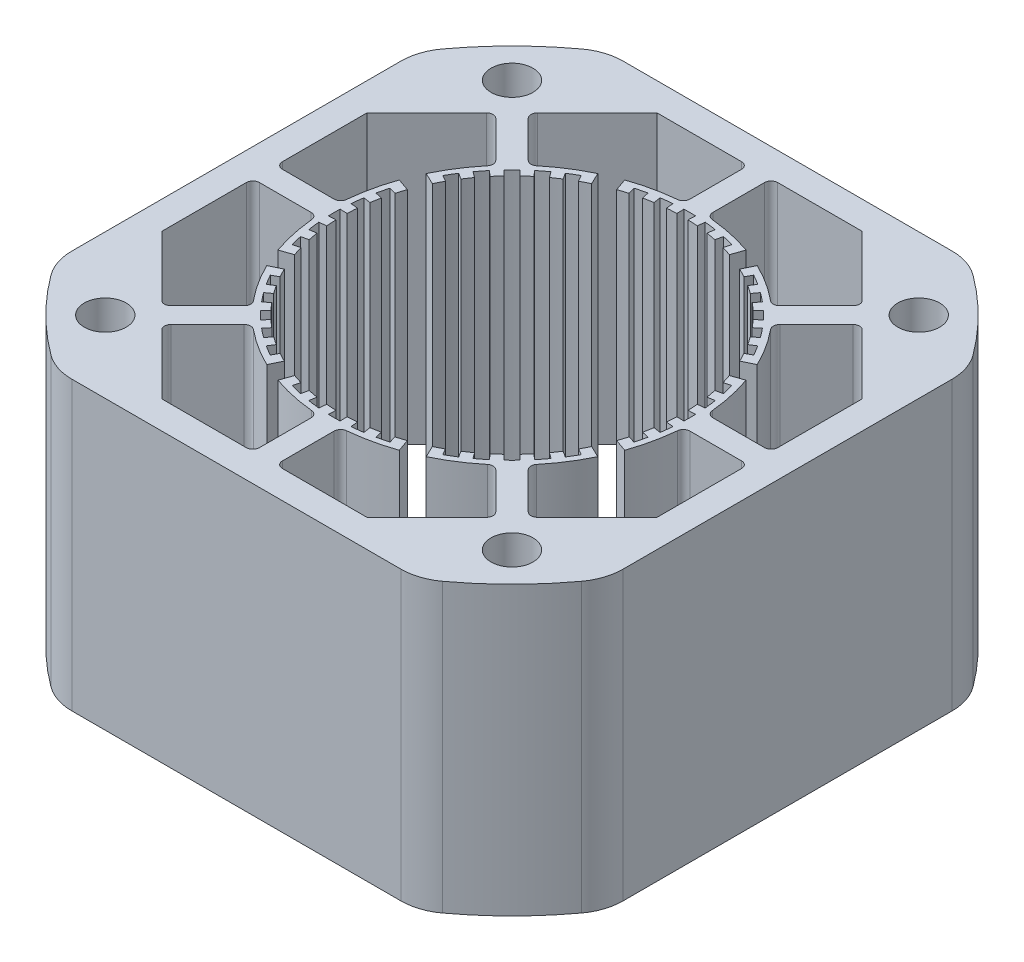
SolidWorks part; units mm, degrees
ref_plane "Front" through (0, 0, 0) normal (0, 0, 1) x (1, 0, 0)
ref_plane "Top" through (0, 0, 0) normal (0, 1, 0) x (1, 0, 0)
ref_plane "Right" through (0, 0, 0) normal (1, 0, 0) x (0, 0, -1)
ref_plane "Plane1" through (0, 10.95, 0) normal (0, 1, 0) x (1, 0, 0)
sketch "Sketch1" plane through (0, 10.95, 0) normal (0, 1, 0) x (1, 0, 0)
  line L0 (-0.875, -14.4347) -> (-0.875, -18.375)
  line L1 (-1.375, -18.875) -> (-7.8183, -18.875)
  line L2 (-7.8183, -18.875) -> (-12.3744, -14.3189)
  line L3 (-12.3744, -13.6118) -> (-9.5881, -10.8256)
  line L4 (-6.0745, -12.6135) -> (-5.6406, -11.7126)
  line L5 (-6.3066, -11.3678) -> (-6.5735, -11.8487)
  line L6 (-7.3337, -11.3938) -> (-7.036, -10.9313)
  line L7 (-7.6547, -10.5074) -> (-7.9786, -10.9519)
  line L8 (-8.6772, -10.4071) -> (-8.325, -9.9847)
  line L9 (-8.887, -9.488) -> (-9.2629, -9.8894)
  line L10 (-9.8894, -9.2629) -> (-9.488, -8.887)
  line L11 (-9.9847, -8.325) -> (-10.4071, -8.6772)
  line L12 (-10.9519, -7.9786) -> (-10.5074, -7.6547)
  line L13 (-10.9313, -7.036) -> (-11.3938, -7.3337)
  line L14 (-11.8487, -6.5735) -> (-11.3678, -6.3066)
  line L15 (-11.7126, -5.6406) -> (-12.6135, -6.0745)
  line L16 (-10.8256, -9.5881) -> (-13.6118, -12.3744)
  line L17 (-14.3189, -12.3744) -> (-18.875, -7.8183)
  line L18 (-18.875, -7.8183) -> (-18.875, -1.375)
  line L19 (-18.375, -0.875) -> (-14.4347, -0.875)
  line L20 (-13.2144, -4.6238) -> (-12.2705, -4.2935)
  line L21 (-12.4977, -3.5788) -> (-13.0264, -3.7302)
  line L22 (-13.2424, -2.8709) -> (-12.7049, -2.7544)
  line L23 (-12.8426, -2.0171) -> (-13.3859, -2.1025)
  line L24 (-13.4947, -1.2232) -> (-12.9469, -1.1736)
  line L25 (-12.9931, -0.425) -> (-13.5428, -0.443)
  line L26 (-13.5428, 0.443) -> (-12.9931, 0.425)
  line L27 (-12.9469, 1.1736) -> (-13.4947, 1.2232)
  line L28 (-13.3859, 2.1025) -> (-12.8426, 2.0171)
  line L29 (-12.7049, 2.7544) -> (-13.2424, 2.8709)
  line L30 (-13.0264, 3.7302) -> (-12.4977, 3.5788)
  line L31 (-12.2705, 4.2935) -> (-13.2144, 4.6238)
  line L32 (-14.4347, 0.875) -> (-18.375, 0.875)
  line L33 (-18.875, 1.375) -> (-18.875, 7.8183)
  line L34 (-18.875, 7.8183) -> (-14.3189, 12.3744)
  line L35 (-13.6118, 12.3744) -> (-10.8256, 9.5881)
  line L36 (-12.6135, 6.0745) -> (-11.7126, 5.6406)
  line L37 (-11.3678, 6.3066) -> (-11.8487, 6.5735)
  line L38 (-11.3938, 7.3337) -> (-10.9313, 7.036)
  line L39 (-10.5074, 7.6547) -> (-10.9519, 7.9786)
  line L40 (-10.4071, 8.6772) -> (-9.9847, 8.325)
  line L41 (-9.488, 8.887) -> (-9.8894, 9.2629)
  line L42 (-9.2629, 9.8894) -> (-8.887, 9.488)
  line L43 (-8.325, 9.9847) -> (-8.6772, 10.4071)
  line L44 (-7.9786, 10.9519) -> (-7.6547, 10.5074)
  line L45 (-7.036, 10.9313) -> (-7.3337, 11.3938)
  line L46 (-6.5735, 11.8487) -> (-6.3066, 11.3678)
  line L47 (-5.6406, 11.7126) -> (-6.0745, 12.6135)
  line L48 (-9.5881, 10.8256) -> (-12.3744, 13.6118)
  line L49 (-12.3744, 14.3189) -> (-7.8183, 18.875)
  line L50 (-7.8183, 18.875) -> (-1.375, 18.875)
  line L51 (-0.875, 18.375) -> (-0.875, 14.4347)
  line L52 (-4.6238, 13.2144) -> (-4.2935, 12.2705)
  line L53 (-3.5788, 12.4977) -> (-3.7302, 13.0264)
  line L54 (-2.8709, 13.2424) -> (-2.7544, 12.7049)
  line L55 (-2.0171, 12.8426) -> (-2.1025, 13.3859)
  line L56 (-1.2232, 13.4947) -> (-1.1736, 12.9469)
  line L57 (-0.425, 12.9931) -> (-0.443, 13.5428)
  line L58 (0.443, 13.5428) -> (0.425, 12.9931)
  line L59 (1.1736, 12.9469) -> (1.2232, 13.4947)
  line L60 (2.1025, 13.3859) -> (2.0171, 12.8426)
  line L61 (2.7544, 12.7049) -> (2.8709, 13.2424)
  line L62 (3.7302, 13.0264) -> (3.5788, 12.4977)
  line L63 (4.2935, 12.2705) -> (4.6238, 13.2144)
  line L64 (0.875, 14.4347) -> (0.875, 18.375)
  line L65 (1.375, 18.875) -> (7.8183, 18.875)
  line L66 (7.8183, 18.875) -> (12.3744, 14.3189)
  line L67 (12.3744, 13.6118) -> (9.5881, 10.8256)
  line L68 (6.0745, 12.6135) -> (5.6406, 11.7126)
  line L69 (6.3066, 11.3678) -> (6.5735, 11.8487)
  line L70 (7.3337, 11.3938) -> (7.036, 10.9313)
  line L71 (7.6547, 10.5074) -> (7.9786, 10.9519)
  line L72 (8.6772, 10.4071) -> (8.325, 9.9847)
  line L73 (8.887, 9.488) -> (9.2629, 9.8894)
  line L74 (9.8894, 9.2629) -> (9.488, 8.887)
  line L75 (9.9847, 8.325) -> (10.4071, 8.6772)
  line L76 (10.9519, 7.9786) -> (10.5074, 7.6547)
  line L77 (10.9313, 7.036) -> (11.3938, 7.3337)
  line L78 (11.8487, 6.5735) -> (11.3678, 6.3066)
  line L79 (11.7126, 5.6406) -> (12.6135, 6.0745)
  line L80 (10.8256, 9.5881) -> (13.6118, 12.3744)
  line L81 (14.3189, 12.3744) -> (18.875, 7.8183)
  line L82 (18.875, 7.8183) -> (18.875, 1.375)
  line L83 (18.375, 0.875) -> (14.4347, 0.875)
  line L84 (13.2144, 4.6238) -> (12.2705, 4.2935)
  line L85 (12.4977, 3.5788) -> (13.0264, 3.7302)
  line L86 (13.2424, 2.8709) -> (12.7049, 2.7544)
  line L87 (12.8426, 2.0171) -> (13.3859, 2.1025)
  line L88 (13.4947, 1.2232) -> (12.9469, 1.1736)
  line L89 (12.9931, 0.425) -> (13.5428, 0.443)
  line L90 (13.5428, -0.443) -> (12.9931, -0.425)
  line L91 (12.9469, -1.1736) -> (13.4947, -1.2232)
  line L92 (13.3859, -2.1025) -> (12.8426, -2.0171)
  line L93 (12.7049, -2.7544) -> (13.2424, -2.8709)
  line L94 (13.0264, -3.7302) -> (12.4977, -3.5788)
  line L95 (12.2705, -4.2935) -> (13.2144, -4.6238)
  line L96 (14.4347, -0.875) -> (18.375, -0.875)
  line L97 (18.875, -1.375) -> (18.875, -7.8183)
  line L98 (18.875, -7.8183) -> (14.3189, -12.3744)
  line L99 (13.6118, -12.3744) -> (10.8256, -9.5881)
  line L100 (12.6135, -6.0745) -> (11.7126, -5.6406)
  line L101 (11.3678, -6.3066) -> (11.8487, -6.5735)
  line L102 (11.3938, -7.3337) -> (10.9313, -7.036)
  line L103 (10.5074, -7.6547) -> (10.9519, -7.9786)
  line L104 (10.4071, -8.6772) -> (9.9847, -8.325)
  line L105 (9.488, -8.887) -> (9.8894, -9.2629)
  line L106 (9.2629, -9.8894) -> (8.887, -9.488)
  line L107 (8.325, -9.9847) -> (8.6772, -10.4071)
  line L108 (7.9786, -10.9519) -> (7.6547, -10.5074)
  line L109 (7.036, -10.9313) -> (7.3337, -11.3938)
  line L110 (6.5735, -11.8487) -> (6.3066, -11.3678)
  line L111 (5.6406, -11.7126) -> (6.0745, -12.6135)
  line L112 (9.5881, -10.8256) -> (12.3744, -13.6118)
  line L113 (12.3744, -14.3189) -> (7.8183, -18.875)
  line L114 (7.8183, -18.875) -> (1.375, -18.875)
  line L115 (0.875, -18.375) -> (0.875, -14.4347)
  line L116 (4.6238, -13.2144) -> (4.2935, -12.2705)
  line L117 (3.5788, -12.4977) -> (3.7302, -13.0264)
  line L118 (2.8709, -13.2424) -> (2.7544, -12.7049)
  line L119 (2.0171, -12.8426) -> (2.1025, -13.3859)
  line L120 (1.2232, -13.4947) -> (1.1736, -12.9469)
  line L121 (0.425, -12.9931) -> (0.443, -13.5428)
  line L122 (-0.443, -13.5428) -> (-0.425, -12.9931)
  line L123 (-1.1736, -12.9469) -> (-1.2232, -13.4947)
  line L124 (-2.1025, -13.3859) -> (-2.0171, -12.8426)
  line L125 (-2.7544, -12.7049) -> (-2.8709, -13.2424)
  line L126 (-3.7302, -13.0264) -> (-3.5788, -12.4977)
  line L127 (-4.2935, -12.2705) -> (-4.6238, -13.2144)
  line L128 (21, -12.5406) -> (21, 12.5406)
  line L129 (12.5406, 21) -> (-12.5406, 21)
  line L130 (-21, 12.5406) -> (-21, -12.5406)
  line L131 (-12.5406, -21) -> (12.5406, -21)
  arc A0 (-0.875, -18.375) -> (-1.375, -18.875) centre (-1.375, -18.375) cw
  arc A1 (-12.3744, -14.3189) -> (-12.3744, -13.6118) centre (-12.0208, -13.9654) cw
  arc A2 (-9.5881, -10.8256) -> (-8.9161, -10.7936) centre (-9.2346, -11.1791) cw
  arc A3 (-8.9161, -10.7936) -> (-6.0745, -12.6135) centre (0, 0) ccw
  arc A4 (-5.6406, -11.7126) -> (-6.3066, -11.3678) centre (0, 0) cw
  arc A5 (-6.5735, -11.8487) -> (-7.3337, -11.3938) centre (0, 0) cw
  arc A6 (-7.036, -10.9313) -> (-7.6547, -10.5074) centre (0, 0) cw
  arc A7 (-7.9786, -10.9519) -> (-8.6772, -10.4071) centre (0, 0) cw
  arc A8 (-8.325, -9.9847) -> (-8.887, -9.488) centre (0, 0) cw
  arc A9 (-9.2629, -9.8894) -> (-9.8894, -9.2629) centre (0, 0) cw
  arc A10 (-9.488, -8.887) -> (-9.9847, -8.325) centre (0, 0) cw
  arc A11 (-10.4071, -8.6772) -> (-10.9519, -7.9786) centre (0, 0) cw
  arc A12 (-10.5074, -7.6547) -> (-10.9313, -7.036) centre (0, 0) cw
  arc A13 (-11.3938, -7.3337) -> (-11.8487, -6.5735) centre (0, 0) cw
  arc A14 (-11.3678, -6.3066) -> (-11.7126, -5.6406) centre (0, 0) cw
  arc A15 (-12.6135, -6.0745) -> (-10.7936, -8.9161) centre (0, 0) ccw
  arc A16 (-10.7936, -8.9161) -> (-10.8256, -9.5881) centre (-11.1791, -9.2346) cw
  arc A17 (-13.6118, -12.3744) -> (-14.3189, -12.3744) centre (-13.9654, -12.0208) cw
  arc A18 (-18.875, -1.375) -> (-18.375, -0.875) centre (-18.375, -1.375) cw
  arc A19 (-14.4347, -0.875) -> (-13.9369, -1.3276) centre (-14.4347, -1.375) cw
  arc A20 (-13.9369, -1.3276) -> (-13.2144, -4.6238) centre (0, 0) ccw
  arc A21 (-12.2705, -4.2935) -> (-12.4977, -3.5788) centre (0, 0) cw
  arc A22 (-13.0264, -3.7302) -> (-13.2424, -2.8709) centre (0, 0) cw
  arc A23 (-12.7049, -2.7544) -> (-12.8426, -2.0171) centre (0, 0) cw
  arc A24 (-13.3859, -2.1025) -> (-13.4947, -1.2232) centre (0, 0) cw
  arc A25 (-12.9469, -1.1736) -> (-12.9931, -0.425) centre (0, 0) cw
  arc A26 (-13.5428, -0.443) -> (-13.5428, 0.443) centre (0, 0) cw
  arc A27 (-12.9931, 0.425) -> (-12.9469, 1.1736) centre (0, 0) cw
  arc A28 (-13.4947, 1.2232) -> (-13.3859, 2.1025) centre (0, 0) cw
  arc A29 (-12.8426, 2.0171) -> (-12.7049, 2.7544) centre (0, 0) cw
  arc A30 (-13.2424, 2.8709) -> (-13.0264, 3.7302) centre (0, 0) cw
  arc A31 (-12.4977, 3.5788) -> (-12.2705, 4.2935) centre (0, 0) cw
  arc A32 (-13.2144, 4.6238) -> (-13.9369, 1.3276) centre (0, 0) ccw
  arc A33 (-13.9369, 1.3276) -> (-14.4347, 0.875) centre (-14.4347, 1.375) cw
  arc A34 (-18.375, 0.875) -> (-18.875, 1.375) centre (-18.375, 1.375) cw
  arc A35 (-14.3189, 12.3744) -> (-13.6118, 12.3744) centre (-13.9654, 12.0208) cw
  arc A36 (-10.8256, 9.5881) -> (-10.7936, 8.9161) centre (-11.1791, 9.2346) cw
  arc A37 (-10.7936, 8.9161) -> (-12.6135, 6.0745) centre (0, 0) ccw
  arc A38 (-11.7126, 5.6406) -> (-11.3678, 6.3066) centre (0, 0) cw
  arc A39 (-11.8487, 6.5735) -> (-11.3938, 7.3337) centre (0, 0) cw
  arc A40 (-10.9313, 7.036) -> (-10.5074, 7.6547) centre (0, 0) cw
  arc A41 (-10.9519, 7.9786) -> (-10.4071, 8.6772) centre (0, 0) cw
  arc A42 (-9.9847, 8.325) -> (-9.488, 8.887) centre (0, 0) cw
  arc A43 (-9.8894, 9.2629) -> (-9.2629, 9.8894) centre (0, 0) cw
  arc A44 (-8.887, 9.488) -> (-8.325, 9.9847) centre (0, 0) cw
  arc A45 (-8.6772, 10.4071) -> (-7.9786, 10.9519) centre (0, 0) cw
  arc A46 (-7.6547, 10.5074) -> (-7.036, 10.9313) centre (0, 0) cw
  arc A47 (-7.3337, 11.3938) -> (-6.5735, 11.8487) centre (0, 0) cw
  arc A48 (-6.3066, 11.3678) -> (-5.6406, 11.7126) centre (0, 0) cw
  arc A49 (-6.0745, 12.6135) -> (-8.9161, 10.7936) centre (0, 0) ccw
  arc A50 (-8.9161, 10.7936) -> (-9.5881, 10.8256) centre (-9.2346, 11.1791) cw
  arc A51 (-12.3744, 13.6118) -> (-12.3744, 14.3189) centre (-12.0208, 13.9654) cw
  arc A52 (-1.375, 18.875) -> (-0.875, 18.375) centre (-1.375, 18.375) cw
  arc A53 (-0.875, 14.4347) -> (-1.3276, 13.9369) centre (-1.375, 14.4347) cw
  arc A54 (-1.3276, 13.9369) -> (-4.6238, 13.2144) centre (0, 0) ccw
  arc A55 (-4.2935, 12.2705) -> (-3.5788, 12.4977) centre (0, 0) cw
  arc A56 (-3.7302, 13.0264) -> (-2.8709, 13.2424) centre (0, 0) cw
  arc A57 (-2.7544, 12.7049) -> (-2.0171, 12.8426) centre (0, 0) cw
  arc A58 (-2.1025, 13.3859) -> (-1.2232, 13.4947) centre (0, 0) cw
  arc A59 (-1.1736, 12.9469) -> (-0.425, 12.9931) centre (0, 0) cw
  arc A60 (-0.443, 13.5428) -> (0.443, 13.5428) centre (0, 0) cw
  arc A61 (0.425, 12.9931) -> (1.1736, 12.9469) centre (0, 0) cw
  arc A62 (1.2232, 13.4947) -> (2.1025, 13.3859) centre (0, 0) cw
  arc A63 (2.0171, 12.8426) -> (2.7544, 12.7049) centre (0, 0) cw
  arc A64 (2.8709, 13.2424) -> (3.7302, 13.0264) centre (0, 0) cw
  arc A65 (3.5788, 12.4977) -> (4.2935, 12.2705) centre (0, 0) cw
  arc A66 (4.6238, 13.2144) -> (1.3276, 13.9369) centre (0, 0) ccw
  arc A67 (1.3276, 13.9369) -> (0.875, 14.4347) centre (1.375, 14.4347) cw
  arc A68 (0.875, 18.375) -> (1.375, 18.875) centre (1.375, 18.375) cw
  arc A69 (12.3744, 14.3189) -> (12.3744, 13.6118) centre (12.0208, 13.9654) cw
  arc A70 (9.5881, 10.8256) -> (8.9161, 10.7936) centre (9.2346, 11.1791) cw
  arc A71 (8.9161, 10.7936) -> (6.0745, 12.6135) centre (0, 0) ccw
  arc A72 (5.6406, 11.7126) -> (6.3066, 11.3678) centre (0, 0) cw
  arc A73 (6.5735, 11.8487) -> (7.3337, 11.3938) centre (0, 0) cw
  arc A74 (7.036, 10.9313) -> (7.6547, 10.5074) centre (0, 0) cw
  arc A75 (7.9786, 10.9519) -> (8.6772, 10.4071) centre (0, 0) cw
  arc A76 (8.325, 9.9847) -> (8.887, 9.488) centre (0, 0) cw
  arc A77 (9.2629, 9.8894) -> (9.8894, 9.2629) centre (0, 0) cw
  arc A78 (9.488, 8.887) -> (9.9847, 8.325) centre (0, 0) cw
  arc A79 (10.4071, 8.6772) -> (10.9519, 7.9786) centre (0, 0) cw
  arc A80 (10.5074, 7.6547) -> (10.9313, 7.036) centre (0, 0) cw
  arc A81 (11.3938, 7.3337) -> (11.8487, 6.5735) centre (0, 0) cw
  arc A82 (11.3678, 6.3066) -> (11.7126, 5.6406) centre (0, 0) cw
  arc A83 (12.6135, 6.0745) -> (10.7936, 8.9161) centre (0, 0) ccw
  arc A84 (10.7936, 8.9161) -> (10.8256, 9.5881) centre (11.1791, 9.2346) cw
  arc A85 (13.6118, 12.3744) -> (14.3189, 12.3744) centre (13.9654, 12.0208) cw
  arc A86 (18.875, 1.375) -> (18.375, 0.875) centre (18.375, 1.375) cw
  arc A87 (14.4347, 0.875) -> (13.9369, 1.3276) centre (14.4347, 1.375) cw
  arc A88 (13.9369, 1.3276) -> (13.2144, 4.6238) centre (0, 0) ccw
  arc A89 (12.2705, 4.2935) -> (12.4977, 3.5788) centre (0, 0) cw
  arc A90 (13.0264, 3.7302) -> (13.2424, 2.8709) centre (0, 0) cw
  arc A91 (12.7049, 2.7544) -> (12.8426, 2.0171) centre (0, 0) cw
  arc A92 (13.3859, 2.1025) -> (13.4947, 1.2232) centre (0, 0) cw
  arc A93 (12.9469, 1.1736) -> (12.9931, 0.425) centre (0, 0) cw
  arc A94 (13.5428, 0.443) -> (13.5428, -0.443) centre (0, 0) cw
  arc A95 (12.9931, -0.425) -> (12.9469, -1.1736) centre (0, 0) cw
  arc A96 (13.4947, -1.2232) -> (13.3859, -2.1025) centre (0, 0) cw
  arc A97 (12.8426, -2.0171) -> (12.7049, -2.7544) centre (0, 0) cw
  arc A98 (13.2424, -2.8709) -> (13.0264, -3.7302) centre (0, 0) cw
  arc A99 (12.4977, -3.5788) -> (12.2705, -4.2935) centre (0, 0) cw
  arc A100 (13.2144, -4.6238) -> (13.9369, -1.3276) centre (0, 0) ccw
  arc A101 (13.9369, -1.3276) -> (14.4347, -0.875) centre (14.4347, -1.375) cw
  arc A102 (18.375, -0.875) -> (18.875, -1.375) centre (18.375, -1.375) cw
  arc A103 (14.3189, -12.3744) -> (13.6118, -12.3744) centre (13.9654, -12.0208) cw
  arc A104 (10.8256, -9.5881) -> (10.7936, -8.9161) centre (11.1791, -9.2346) cw
  arc A105 (10.7936, -8.9161) -> (12.6135, -6.0745) centre (0, 0) ccw
  arc A106 (11.7126, -5.6406) -> (11.3678, -6.3066) centre (0, 0) cw
  arc A107 (11.8487, -6.5735) -> (11.3938, -7.3337) centre (0, 0) cw
  arc A108 (10.9313, -7.036) -> (10.5074, -7.6547) centre (0, 0) cw
  arc A109 (10.9519, -7.9786) -> (10.4071, -8.6772) centre (0, 0) cw
  arc A110 (9.9847, -8.325) -> (9.488, -8.887) centre (0, 0) cw
  arc A111 (9.8894, -9.2629) -> (9.2629, -9.8894) centre (0, 0) cw
  arc A112 (8.887, -9.488) -> (8.325, -9.9847) centre (0, 0) cw
  arc A113 (8.6772, -10.4071) -> (7.9786, -10.9519) centre (0, 0) cw
  arc A114 (7.6547, -10.5074) -> (7.036, -10.9313) centre (0, 0) cw
  arc A115 (7.3337, -11.3938) -> (6.5735, -11.8487) centre (0, 0) cw
  arc A116 (6.3066, -11.3678) -> (5.6406, -11.7126) centre (0, 0) cw
  arc A117 (6.0745, -12.6135) -> (8.9161, -10.7936) centre (0, 0) ccw
  arc A118 (8.9161, -10.7936) -> (9.5881, -10.8256) centre (9.2346, -11.1791) cw
  arc A119 (12.3744, -13.6118) -> (12.3744, -14.3189) centre (12.0208, -13.9654) cw
  arc A120 (1.375, -18.875) -> (0.875, -18.375) centre (1.375, -18.375) cw
  arc A121 (0.875, -14.4347) -> (1.3276, -13.9369) centre (1.375, -14.4347) cw
  arc A122 (1.3276, -13.9369) -> (4.6238, -13.2144) centre (0, 0) ccw
  arc A123 (4.2935, -12.2705) -> (3.5788, -12.4977) centre (0, 0) cw
  arc A124 (3.7302, -13.0264) -> (2.8709, -13.2424) centre (0, 0) cw
  arc A125 (2.7544, -12.7049) -> (2.0171, -12.8426) centre (0, 0) cw
  arc A126 (2.1025, -13.3859) -> (1.2232, -13.4947) centre (0, 0) cw
  arc A127 (1.1736, -12.9469) -> (0.425, -12.9931) centre (0, 0) cw
  arc A128 (0.443, -13.5428) -> (-0.443, -13.5428) centre (0, 0) cw
  arc A129 (-0.425, -12.9931) -> (-1.1736, -12.9469) centre (0, 0) cw
  arc A130 (-1.2232, -13.4947) -> (-2.1025, -13.3859) centre (0, 0) cw
  arc A131 (-2.0171, -12.8426) -> (-2.7544, -12.7049) centre (0, 0) cw
  arc A132 (-2.8709, -13.2424) -> (-3.7302, -13.0264) centre (0, 0) cw
  arc A133 (-3.5788, -12.4977) -> (-4.2935, -12.2705) centre (0, 0) cw
  arc A134 (-4.6238, -13.2144) -> (-1.3276, -13.9369) centre (0, 0) ccw
  arc A135 (-1.3276, -13.9369) -> (-0.875, -14.4347) centre (-1.375, -14.4347) cw
  arc A136 (14.9151, -20.2189) -> (20.2189, -14.9151) centre (0, 0) ccw
  arc A137 (20.2189, -14.9151) -> (21, -12.5406) centre (17, -12.5406) ccw
  arc A138 (21, 12.5406) -> (20.2189, 14.9151) centre (17, 12.5406) ccw
  arc A139 (20.2189, 14.9151) -> (14.9151, 20.2189) centre (0, 0) ccw
  arc A140 (14.9151, 20.2189) -> (12.5406, 21) centre (12.5406, 17) ccw
  arc A141 (-12.5406, 21) -> (-14.9151, 20.2189) centre (-12.5406, 17) ccw
  arc A142 (-14.9151, 20.2189) -> (-20.2189, 14.9151) centre (0, 0) ccw
  arc A143 (-20.2189, 14.9151) -> (-21, 12.5406) centre (-17, 12.5406) ccw
  arc A144 (-21, -12.5406) -> (-20.2189, -14.9151) centre (-17, -12.5406) ccw
  arc A145 (-20.2189, -14.9151) -> (-14.9151, -20.2189) centre (0, 0) ccw
  arc A146 (-14.9151, -20.2189) -> (-12.5406, -21) centre (-12.5406, -17) ccw
  arc A147 (12.5406, -21) -> (14.9151, -20.2189) centre (12.5406, -17) ccw
sketch "Sketch10" plane through (0, 0, 0) normal (0, 1, 0) x (1, 0, 0)
  line L4 (12.5406, 21) -> (-12.5406, 21)
  line L5 (-21, 12.5406) -> (-21, -12.5406)
  line L6 (-12.5406, -21) -> (12.5406, -21)
  line L7 (21, -12.5406) -> (21, 12.5406)
  line L10 (7.8183, -18.875) -> (18.875, -7.8183)
  line L11 (18.875, -7.8183) -> (18.875, 7.8183)
  line L12 (18.875, 7.8183) -> (7.8183, 18.875)
  line L13 (7.8183, 18.875) -> (-7.8183, 18.875)
  line L14 (-7.8183, 18.875) -> (-18.875, 7.8183)
  line L15 (-18.875, 7.8183) -> (-18.875, -7.8183)
  line L16 (-18.875, -7.8183) -> (-7.8183, -18.875)
  line L17 (0, 21) -> (0, 0) construction
  line L18 (0, 0) -> (21, 0) construction
  line L19 (-7.8183, -18.875) -> (7.8183, -18.875)
  arc A12 (-12.5406, 21) -> (-14.9151, 20.2189) centre (-12.5406, 17) ccw
  arc A13 (-14.9151, 20.2189) -> (-20.2189, 14.9151) centre (0, 0) ccw
  arc A14 (-20.2189, 14.9151) -> (-21, 12.5406) centre (-17, 12.5406) ccw
  arc A15 (-21, -12.5406) -> (-20.2189, -14.9151) centre (-17, -12.5406) ccw
  arc A16 (-20.2189, -14.9151) -> (-14.9151, -20.2189) centre (0, 0) ccw
  arc A17 (-14.9151, -20.2189) -> (-12.5406, -21) centre (-12.5406, -17) ccw
  arc A18 (12.5406, -21) -> (14.9151, -20.2189) centre (12.5406, -17) ccw
  arc A19 (14.9151, -20.2189) -> (20.2189, -14.9151) centre (0, 0) ccw
  arc A20 (20.2189, -14.9151) -> (21, -12.5406) centre (17, -12.5406) ccw
  arc A21 (21, 12.5406) -> (20.2189, 14.9151) centre (17, 12.5406) ccw
  arc A22 (20.2189, 14.9151) -> (14.9151, 20.2189) centre (0, 0) ccw
  arc A23 (14.9151, 20.2189) -> (12.5406, 21) centre (12.5406, 17) ccw
  circle A24 centre (0, 0) radius 18.875 construction
  point P26 (-15.5, 15.5)
  point P39 (15.5, 15.5)
  point P40 (15.5, -15.5)
  point P41 (-15.5, -15.5)
  dimension "D3" = 25.125
  dimension "D4" = 4
  dimension "D1" = 42
  dimension "D2" = 42
  dimension "D5" = 37.75
  dimension "D6" = 31
  dimension "D7" = 31
extrude "Boss-Extrude2" add sketch "Sketch10" along normal blind 21.9
sketch "Sketch11" plane through (0, 0, 0) normal (0, 1, 0) x (1, 0, 0)
  line L1 (0, 0) -> (0, 24.4906) construction
  line L3 (-0.875, 18.375) -> (-0.875, 14.4347)
  line L5 (0.875, 14.4347) -> (0.875, 18.375)
  line L17 (4.2935, 12.2705) -> (4.6238, 13.2144)
  line L18 (3.7302, 13.0264) -> (3.5788, 12.4977)
  line L19 (2.7544, 12.7049) -> (2.8709, 13.2424)
  line L20 (2.1025, 13.3859) -> (2.0171, 12.8426)
  line L21 (1.1736, 12.9469) -> (1.2232, 13.4947)
  line L22 (0.443, 13.5428) -> (0.425, 12.9931)
  line L23 (-0.425, 12.9931) -> (-0.443, 13.5428)
  line L24 (-1.1736, 12.9469) -> (-1.2232, 13.4947)
  line L25 (-2.1025, 13.3859) -> (-2.0171, 12.8426)
  line L26 (-2.7544, 12.7049) -> (-2.8709, 13.2424)
  line L27 (-3.7302, 13.0264) -> (-3.5788, 12.4977)
  line L28 (-4.6238, 13.2144) -> (-4.2935, 12.2705)
  line L29 (1.375, 18.875) -> (-1.375, 18.875)
  line L30 (7.8183, 18.875) -> (-7.8183, 18.875) construction
  arc A0 (4.6238, 13.2144) -> (1.3276, 13.9369) centre (0, 0) ccw
  arc A4 (-0.875, 18.375) -> (-1.375, 18.875) centre (-1.375, 18.375) ccw
  arc A5 (-1.3276, 13.9369) -> (-0.875, 14.4347) centre (-1.375, 14.4347) ccw
  arc A8 (1.375, 18.875) -> (0.875, 18.375) centre (1.375, 18.375) ccw
  arc A9 (0.875, 14.4347) -> (1.3276, 13.9369) centre (1.375, 14.4347) ccw
  arc A21 (4.2935, 12.2705) -> (3.5788, 12.4977) centre (0, 0) ccw
  arc A22 (3.7302, 13.0264) -> (2.8709, 13.2424) centre (0, 0) ccw
  arc A23 (2.7544, 12.7049) -> (2.0171, 12.8426) centre (0, 0) ccw
  arc A24 (2.1025, 13.3859) -> (1.2232, 13.4947) centre (0, 0) ccw
  arc A25 (1.1736, 12.9469) -> (0.425, 12.9931) centre (0, 0) ccw
  arc A26 (0.443, 13.5428) -> (-0.443, 13.5428) centre (0, 0) ccw
  arc A27 (-0.425, 12.9931) -> (-1.1736, 12.9469) centre (0, 0) ccw
  arc A28 (-1.2232, 13.4947) -> (-2.1025, 13.3859) centre (0, 0) ccw
  arc A29 (-2.0171, 12.8426) -> (-2.7544, 12.7049) centre (0, 0) ccw
  arc A30 (-2.8709, 13.2424) -> (-3.7302, 13.0264) centre (0, 0) ccw
  arc A31 (-3.5788, 12.4977) -> (-4.2935, 12.2705) centre (0, 0) ccw
  arc A32 (-1.3276, 13.9369) -> (-4.6238, 13.2144) centre (0, 0) ccw
  dimension "D2" = 0.5
  dimension "D3" = 14
  dimension "D4" = 1
  dimension "D5" = 0.45
  dimension "D1" = 1.75
  dimension "D6" = 0.85
  dimension "D7" = 0.85
  dimension "D8" = 0.75
  dimension "D9" = 0.75
  dimension "D10" = 0.85
  dimension "D11" = 0.75
extrude "Boss-Extrude3" add sketch "Sketch11" along normal up to vertex (21.9 mm away) up to point (7.8183, 21.9, -18.875)
pattern_circular "CirPattern1" count 8 over 360 about axis through (0, 0, 0) along (0, 1, 0) of "Boss-Extrude3"
hole_wizard "Ø3.2 (3.2) Diameter Hole1" positions "Sketch3" profile "Sketch2" hole size "Ø3.2" standard "ANSI Metric" end condition through all
sketch "Sketch3" plane through (0, 21.9, 0) normal (0, -1, 0) x (-1, 0, 0)
  point P0 (-15.5, -15.5)
  point P1 (-15.5, 15.5)
  point P4 (15.5, 15.5)
  point P7 (15.5, -15.5)
sketch "Sketch2" plane through (15.5, 21.9, 15.5) normal (1, 0, 0) x (0, 0, 1)
  line L0 (0, 0) -> (0, 21.9)
  line L1 (0, 21.9) -> (1.6, 21.9)
  line L2 (1.6, 21.9) -> (1.6, 0)
  line L5 (1.6, 0) -> (0, 0)
  line L11 (0, -6.35) -> (0, 107.95) construction
  dimension "Thru Hole Dia." = 3.2
  dimension "Thru Hole Depth" = 21.9
